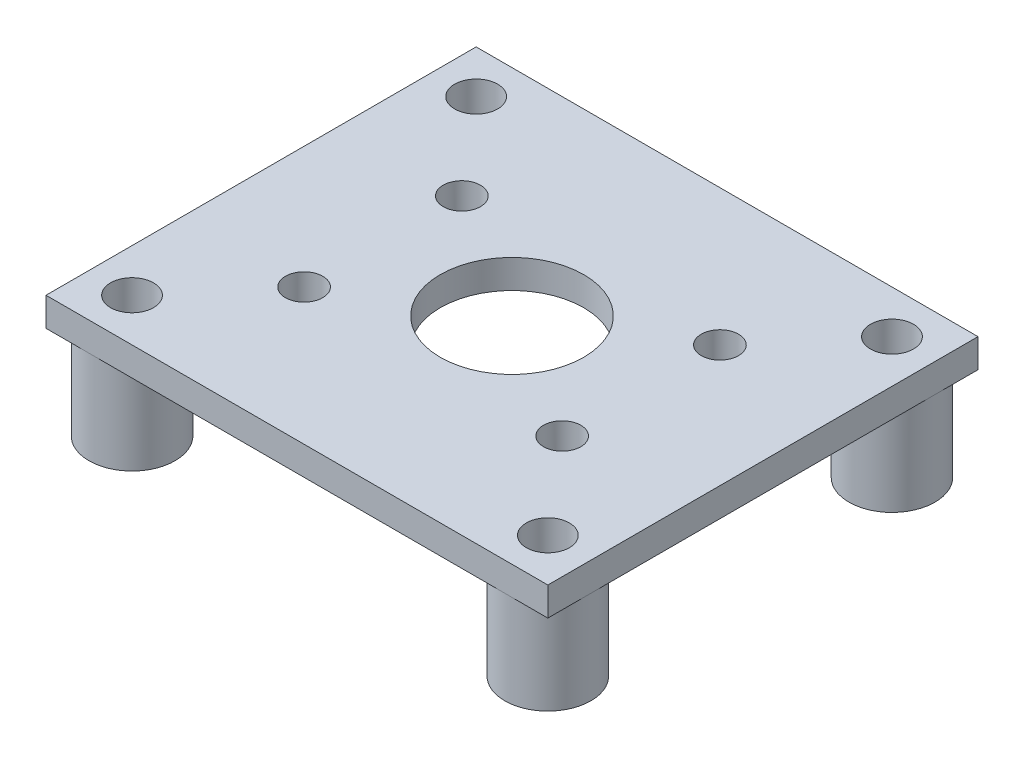
SolidWorks part; units mm, degrees
ref_plane "前视基准面" through (0, 0, 0) normal (0, 0, 1) x (1, 0, 0)
ref_plane "上视基准面" through (0, 0, 0) normal (0, 1, 0) x (1, 0, 0)
ref_plane "右视基准面" through (0, 0, 0) normal (1, 0, 0) x (0, 0, -1)
sketch "Sketch1" plane through (0, 0, 0) normal (0, 1, 0) x (1, 0, 0)
  line L1 (-17.5, 15) -> (17.5, 15)
  line L2 (-17.5, 15) -> (-17.5, -15)
  line L3 (-17.5, -15) -> (17.5, -15)
  line L4 (17.5, 15) -> (17.5, -15)
  line L5 (-17.5, 15) -> (17.5, -15) construction
  line L6 (-17.5, -15) -> (17.5, 15) construction
  point P0 (0, 0)
  dimension "D1" = 35
  dimension "D2" = 30
extrude "Boss-Extrude1" add sketch "Sketch1" along normal blind 2
sketch "Sketch2" plane through (0, 2, 0) normal (0, 1, 0) x (1, 0, 0)
  line L0 (0, 15) -> (0, -15) construction
  line L1 (17.5, 15) -> (-17.5, 15) construction
  line L2 (-17.5, -15) -> (17.5, -15) construction
  line L3 (-17.5, 0) -> (17.5, 0) construction
  line L4 (-17.5, 15) -> (-17.5, -15) construction
  line L5 (17.5, -15) -> (17.5, 15) construction
  circle A0 centre (9, 5.5) radius 1.3
  circle A1 centre (-9, 5.5) radius 1.3
  circle A2 centre (9, -5.5) radius 1.3
  circle A3 centre (-9, -5.5) radius 1.3
  dimension "D1" = 2.6
  dimension "D3" = 5.5
  dimension "D2" = 9
extrude "Cut-Extrude1" cut sketch "Sketch2" against normal up to next
sketch "Sketch3" plane through (0, 0, 0) normal (0, -1, 0) x (1, 0, 0)
  line L0 (-17.5, 15) -> (17.5, 15) construction
  line L1 (-17.5, -15) -> (-17.5, 15) construction
  line L2 (17.5, 15) -> (17.5, -15) construction
  line L3 (-17.5, 0) -> (17.5, 0) construction
  circle A0 centre (-14.5, 12) radius 1.5
  circle A1 centre (14.5, 12) radius 1.5
  circle A2 centre (14.5, -12) radius 1.5
  circle A3 centre (-14.5, -12) radius 1.5
  dimension "D1" = 3
  dimension "D2" = 3
  dimension "D3" = 3
  dimension "D4" = 3
extrude "Cut-Extrude2" cut sketch "Sketch3" against normal up to next
sketch "Sketch4" plane through (0, 0, 0) normal (0, -1, 0) x (1, 0, 0)
  circle A0 centre (-14.5, 12) radius 3
  circle A1 centre (14.5, 12) radius 3
  circle A2 centre (-14.5, -12) radius 3
  circle A3 centre (14.5, -12) radius 3
extrude "Boss-Extrude2" add sketch "Sketch4" along normal blind 6.5
sketch "Sketch5" plane through (0, 0, 0) normal (0, 1, 0) x (1, 0, 0)
  circle A0 centre (-14.5, 12) radius 1.5
  circle A1 centre (14.5, 12) radius 1.5
  circle A2 centre (14.5, -12) radius 1.5
  circle A3 centre (-14.5, -12) radius 1.5
extrude "Cut-Extrude3" cut sketch "Sketch5" against normal up to next
sketch "Sketch6" plane through (0, 0, 0) normal (0, -1, 0) x (1, 0, 0)
  point P0 (0, 0)
sketch "Sketch7" plane through (0, 2, 0) normal (0, 1, 0) x (1, 0, 0)
  line L0 (-9, 5.5) -> (9, -5.5) construction
  line L1 (9, 5.5) -> (-9, -5.5) construction
  circle A0 centre (0, 0) radius 5
extrude "Cut-Extrude4" cut sketch "Sketch7" against normal blind 3
